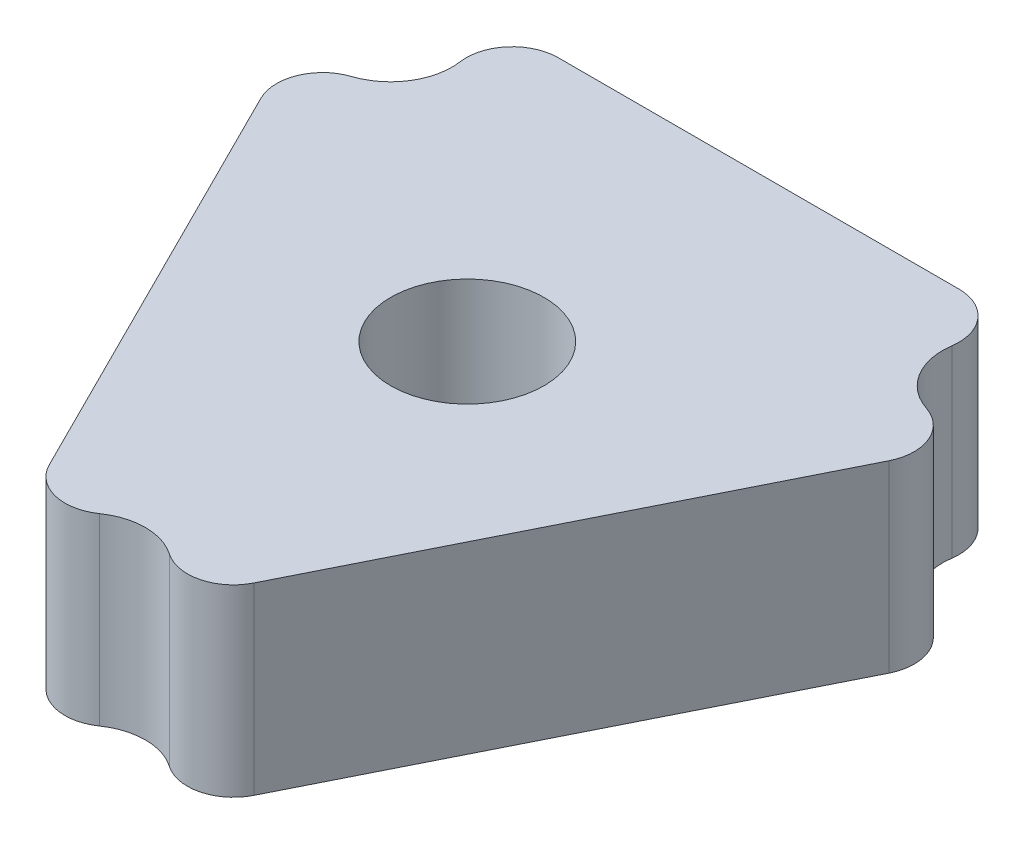
SolidWorks part; units mm, degrees
ref_plane "Front Plane" through (0, 0, 0) normal (0, 0, 1) x (1, 0, 0)
ref_plane "Top Plane" through (0, 0, 0) normal (0, 1, 0) x (1, 0, 0)
ref_plane "Right Plane" through (0, 0, 0) normal (1, 0, 0) x (0, 0, -1)
sketch "Sketch1" plane through (0, 0, 0) normal (0, 1, 0) x (1, 0, 0)
  line L3 (-20.4793, 7.0144) -> (-6.6761, -20.5921)
  line L4 (6.6761, -20.5921) -> (20.4793, 7.0144)
  line L7 (13.0718, 19) -> (-13.0718, 19)
  circle A1 centre (0, 0) radius 5
  arc A2 (16.041, 15.5714) -> (18.7406, 11.2034) centre (20, 15) ccw
  arc A3 (2.2816, -21.7145) -> (-2.2816, -21.7145) centre (0, -25) ccw
  arc A4 (-18.7406, 11.2034) -> (-16.041, 15.5714) centre (-20, 15) ccw
  arc A5 (-6.6761, -20.5921) -> (-2.2816, -21.7145) centre (-3.9928, -19.2504) ccw
  arc A6 (6.6761, -20.5921) -> (2.2816, -21.7145) centre (3.9928, -19.2504) cw
  arc A7 (18.7406, 11.2034) -> (20.4793, 7.0144) centre (17.796, 8.356) cw
  arc A8 (13.0718, 19) -> (16.041, 15.5714) centre (13.0718, 16) cw
  arc A9 (-13.0718, 19) -> (-16.041, 15.5714) centre (-13.0718, 16) ccw
  arc A10 (-20.4793, 7.0144) -> (-18.7406, 11.2034) centre (-17.796, 8.356) cw
  point P11 (0, 0)
  dimension "D1" = 15
  dimension "D2" = 10
  dimension "D3" = 8
  dimension "D5" = 20
  dimension "D6" = 20
  dimension "D7" = 8
  dimension "D8" = 25
  dimension "D9" = 3
  dimension "D4" = 8
extrude "Boss-Extrude1" add sketch "Sketch1" along normal blind 12
